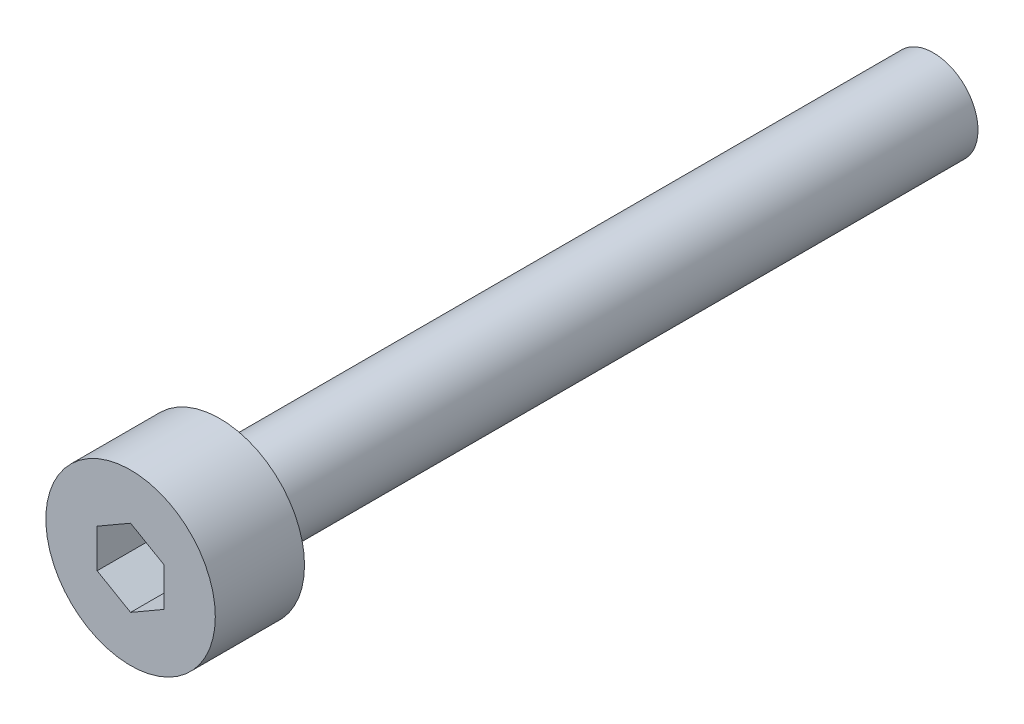
SolidWorks part; units mm, degrees
other "Spring Guide Mount M2 Screw 1"
ref_plane "Front Plane" through (0, 0, 0) normal (0, 0, 1) x (1, 0, 0)
ref_plane "Top Plane" through (0, 0, 0) normal (0, 1, 0) x (1, 0, 0)
ref_plane "Right Plane" through (0, 0, 0) normal (1, 0, 0) x (0, 0, -1)
sketch3d "M2 screw shank profile datum points"
  point P0 (-63.2917, -5.5, 3.2)
  point P1 (-53.2917, -5.5, 3.2)
  point P2 (-63.2917, 4.5, 3.2)
ref_plane "M2 screw shank profile plane" through (0, 0, 3.2) normal (0, 0, 1) x (1, 0, 0)
sketch "M2 screw shank profile" plane through (0, 0, 3.2) normal (0, 0, 1) x (1, 0, 0)
  circle A0 centre (-63.2917, -5.5) radius 1
extrude "M2 screw shank" add sketch "M2 screw shank profile" along normal blind 16 separate body
sketch3d "Socket cap head profile datum points"
  point P0 (-63.2917, -5.5, 19.2)
  point P1 (-53.2917, -5.5, 19.2)
  point P2 (-63.2917, 4.5, 19.2)
ref_plane "Socket cap head profile plane" through (0, 0, 19.2) normal (0, 0, 1) x (1, 0, 0)
sketch "Socket cap head profile" plane through (0, 0, 19.2) normal (0, 0, 1) x (1, 0, 0)
  circle A0 centre (-63.2917, -5.5) radius 1.9
extrude "Socket cap head" add sketch "Socket cap head profile" along normal blind 2
sketch3d "Hex key socket datum points"
  point P0 (-63.2917, -5.5, 20.1)
  point P1 (-53.2917, -5.5, 20.1)
  point P2 (-63.2917, 4.5, 20.1)
ref_plane "Hex key socket plane" through (0, 0, 20.1) normal (0, 0, 1) x (1, 0, 0)
sketch "Hex key socket" plane through (0, 0, 20.1) normal (0, 0, 1) x (1, 0, 0)
  line L0 (-62.5417, -5.067) -> (-63.2917, -4.634)
  line L1 (-63.2917, -4.634) -> (-64.0417, -5.067)
  line L2 (-64.0417, -5.067) -> (-64.0417, -5.933)
  line L3 (-64.0417, -5.933) -> (-63.2917, -6.366)
  line L4 (-63.2917, -6.366) -> (-62.5417, -5.933)
  line L5 (-62.5417, -5.933) -> (-62.5417, -5.067)
extrude "Cut hex key recess" cut sketch "Hex key socket" along normal blind 1.2
